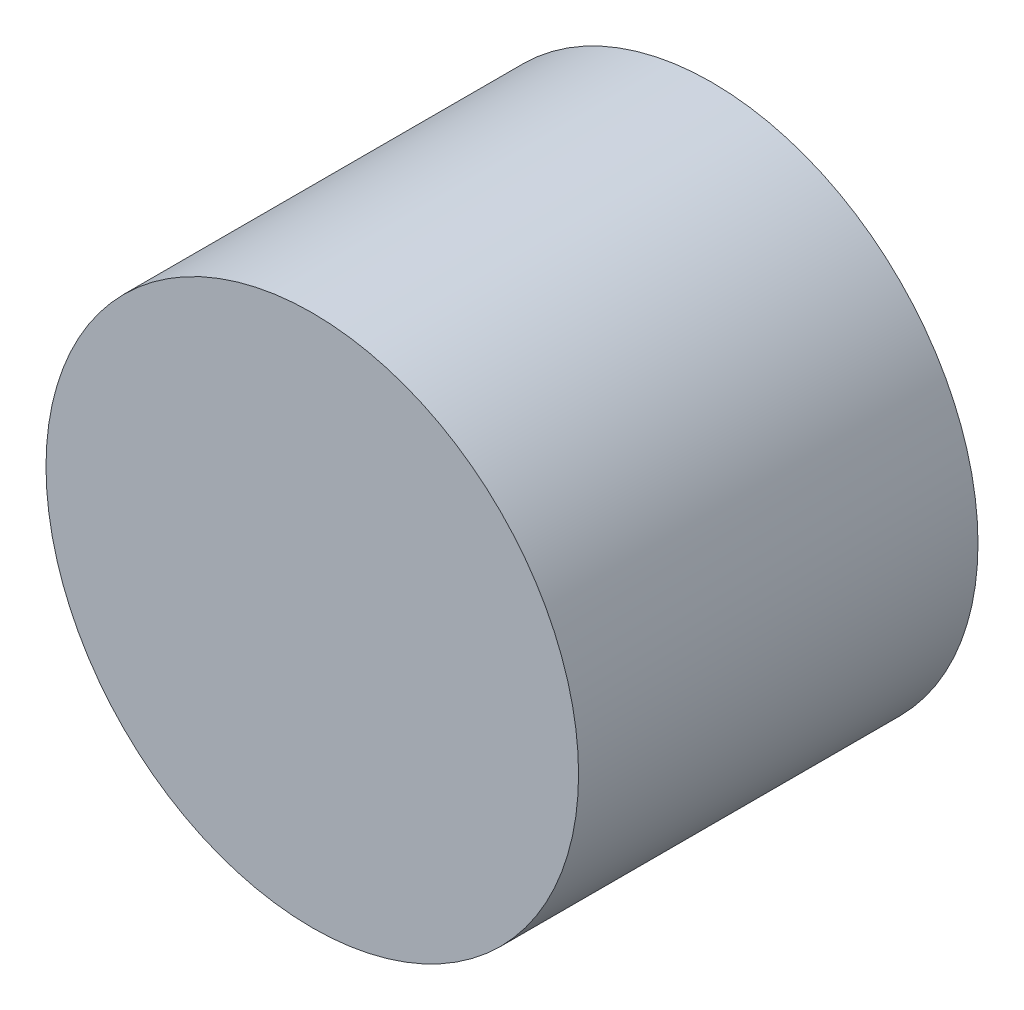
SolidWorks part; units mm, degrees
ref_plane "Přední rovina" through (0, 0, 0) normal (0, 0, 1) x (1, 0, 0)
ref_plane "Horní rovina" through (0, 0, 0) normal (0, 1, 0) x (1, 0, 0)
ref_plane "Pravá rovina" through (0, 0, 0) normal (1, 0, 0) x (0, 0, -1)
sketch "Sketch2" plane through (0, 0, 0) normal (0, 1, 0) x (1, 0, 0)
  line L0 (-10, 0) -> (-10, -10)
  line L3 (0, -30) -> (-20, -30)
  line L4 (-20, -30) -> (-20, 0)
  line L5 (-20, 0) -> (-10, 0)
  line L6 (0, 0) -> (0, -30)
  arc A0 (-10, -10) -> (0, -20) centre (0, -10) ccw
  dimension "D2" = 10
  dimension "D1" = 10
  dimension "D3" = 30
  dimension "D4" = 10
revolve "Revolve3" add sketch "Sketch2" angle 360 about L6
equation "\"R\"= 10"
equation "\"D2@Sketch2\"=\"R\""
equation "\"D3@Sketch2\"=\"R\"*3"
equation "\"D4@Sketch2\"=\"R\""
